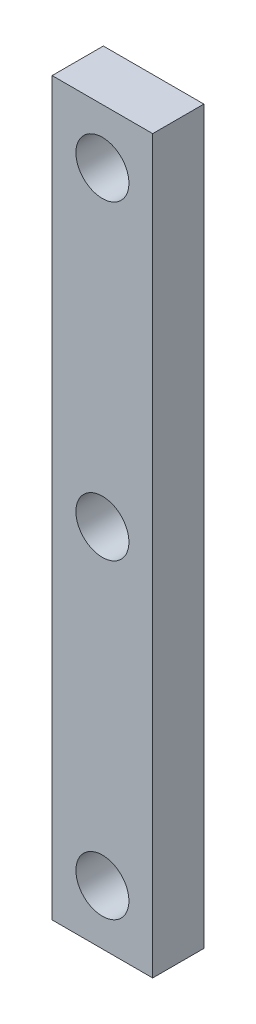
SolidWorks part; units mm, degrees
material "PLA"
ref_plane "Front Plane" through (0, 0, 0) normal (0, 0, 1) x (1, 0, 0)
ref_plane "Top Plane" through (0, 0, 0) normal (0, 1, 0) x (1, 0, 0)
ref_plane "Right Plane" through (0, 0, 0) normal (1, 0, 0) x (0, 0, -1)
sketch "Sketch1" plane through (0, 0, 0) normal (0, 1, 0) x (1, 0, 0)
  line L1 (-2.75, -1.4) -> (2.75, -1.4)
  line L2 (-2.75, -1.4) -> (-2.75, 1.4)
  line L3 (-2.75, 1.4) -> (2.75, 1.4)
  line L4 (2.75, -1.4) -> (2.75, 1.4)
  line L5 (-2.75, -1.4) -> (2.75, 1.4) construction
  line L6 (-2.75, 1.4) -> (2.75, -1.4) construction
  point P4 (0, 0)
  point P5 (0, 0)
  dimension "D1" = 2.8
  dimension "D2" = 5.5
extrude "Boss-Extrude1" add sketch "Sketch1" along normal blind 40
sketch "Sketch2" plane through (0, 0, 1.4) normal (0, 0, 1) x (1, 0, 0)
  line L0 (0, 40) -> (0, 0) construction
  line L1 (-2.75, 40) -> (2.75, 40) construction
  line L2 (-2.75, 20) -> (2.75, 20) construction
  line L3 (-2.75, 40) -> (-2.75, 0) construction
  line L4 (2.75, 40) -> (2.75, 0) construction
hole_wizard "M2.5 Clearance Hole1" positions "Sketch3" profile "Sketch4" hole size "M2.5" standard "ISO" end condition through all
sketch "Sketch3" plane through (0, 0, 1.4) normal (0, 0, 1) x (1, 0, 0)
  line L0 (0, 40) -> (0, 0) construction
  point P0 (0, 20)
  point P4 (0, 37)
  point P6 (0, 3)
  dimension "D1" = 17
  dimension "D2" = 17
sketch "Sketch4" plane through (0, 20, 1.4) normal (1, 0, 0) x (0, -1, 0)
  line L0 (0, 0) -> (0, 2.8)
  line L1 (0, 2.8) -> (1.45, 2.8)
  line L2 (1.45, 2.8) -> (1.45, 0)
  line L5 (1.45, 0) -> (0, 0)
  line L11 (0, -6.35) -> (0, 107.95) construction
  dimension "Thru Hole Dia." = 2.9
  dimension "Thru Hole Depth" = 2.8
